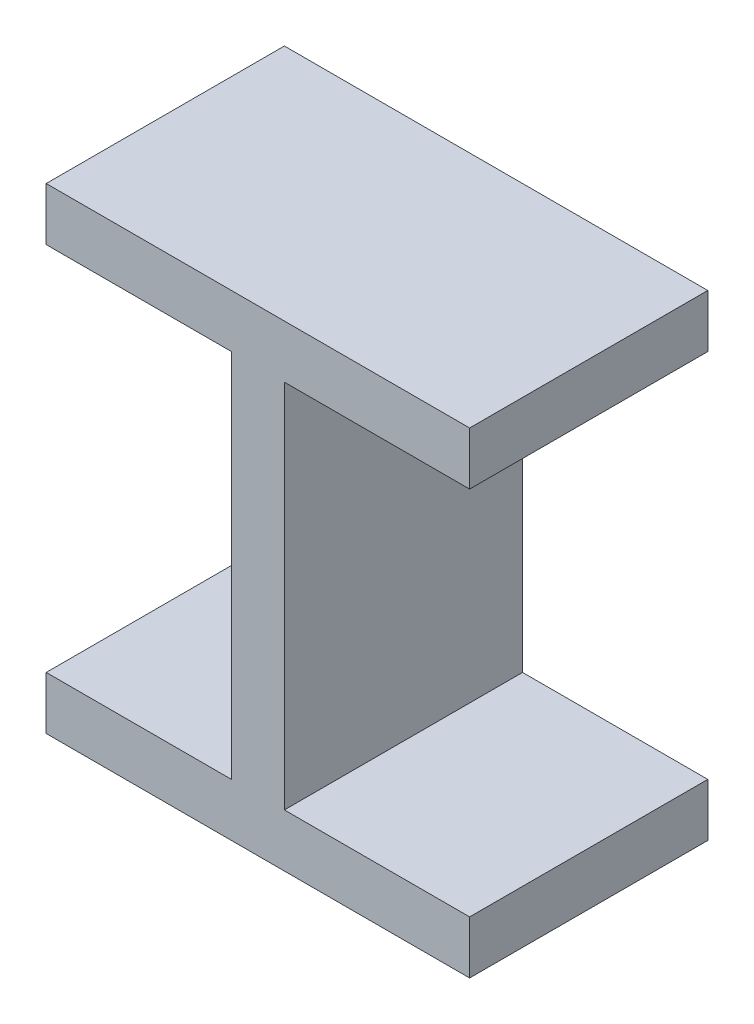
SolidWorks part; units mm, degrees
ref_plane "Front Plane" through (0, 0, 0) normal (0, 0, 1) x (1, 0, 0)
ref_plane "Top Plane" through (0, 0, 0) normal (0, 1, 0) x (1, 0, 0)
ref_plane "Right Plane" through (0, 0, 0) normal (1, 0, 0) x (0, 0, -1)
sketch "Sketch1" plane through (0, 0, 0) normal (0, 0, 1) x (1, 0, 0)
  line L0 (0, 0) -> (73614.4689, 0) construction
  line L1 (0, 0) -> (0, 73614.4689) construction
  line L2 (80, -90) -> (-80, -90)
  line L3 (-80, -90) -> (-80, -70)
  line L4 (-80, -70) -> (-10, -70)
  line L5 (-10, -70) -> (-10, 70)
  line L6 (-10, 70) -> (-80, 70)
  line L7 (-80, 70) -> (-80, 90)
  line L8 (-80, 90) -> (80, 90)
  line L9 (80, -90) -> (80, -70)
  line L10 (80, 70) -> (80, 90)
  line L11 (10, 70) -> (80, 70)
  line L12 (10, -70) -> (10, 70)
  line L13 (80, -70) -> (10, -70)
  point P13 (-80, -80)
  point P14 (80, -80)
  point P18 (0, 90)
  point P21 (0, 0)
  dimension "D1" = 160
  dimension "D2" = 20
  dimension "D3" = 140
  dimension "D4" = 20
  dimension "D5" = 20
extrude "Boss-Extrude1" add sketch "Sketch1" along normal blind 90
